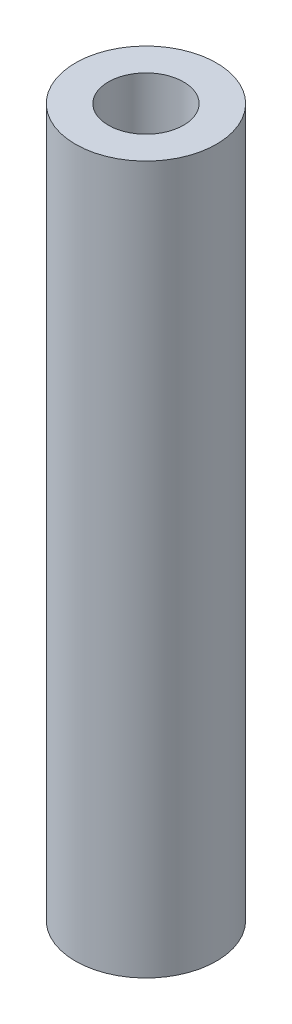
SolidWorks part; units mm, degrees
material "1060 합금"
ref_plane "정면" through (0, 0, 0) normal (0, 0, 1) x (1, 0, 0)
ref_plane "윗면" through (0, 0, 0) normal (0, 1, 0) x (1, 0, 0)
ref_plane "우측면" through (0, 0, 0) normal (1, 0, 0) x (0, 0, -1)
sketch "스케치1" plane through (0, 0, 0) normal (0, 1, 0) x (1, 0, 0)
  circle A0 centre (0, 0) radius 7.5
  dimension "D1" = 15
extrude "보스-돌출1" add sketch "스케치1" against normal blind 75.26
sketch "스케치3" plane through (0, 0, 0) normal (0, 1, 0) x (1, 0, 0)
  circle A0 centre (0, 0) radius 4
  dimension "D1" = 8
extrude "컷-돌출1" cut sketch "스케치3" against normal blind 21.36
